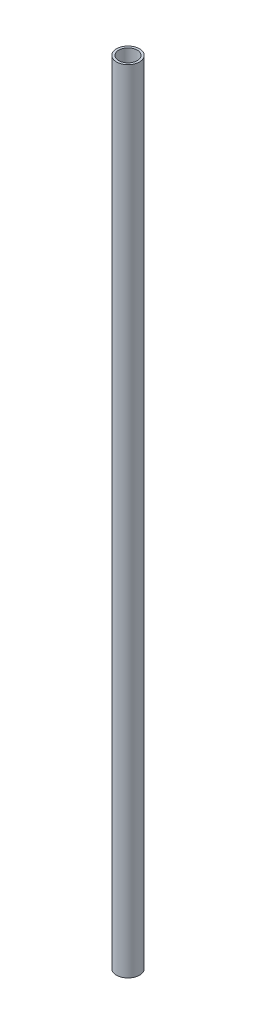
SolidWorks part; units mm, degrees
material "6061-T6 (SS)"
ref_plane "Front Plane" through (0, 0, 0) normal (0, 0, 1) x (1, 0, 0)
ref_plane "Top Plane" through (0, 0, 0) normal (0, 1, 0) x (1, 0, 0)
ref_plane "Right Plane" through (0, 0, 0) normal (1, 0, 0) x (0, 0, -1)
sketch "Sketch1" plane through (0, 0, 0) normal (0, 1, 0) x (1, 0, 0)
  circle A0 centre (0, 0) radius 6.35
  circle A1 centre (0, 0) radius 5.1054
  dimension "D1" = 12.7
  dimension "D2" = 10.2108
extrude "Boss-Extrude1" add sketch "Sketch1" along normal blind 438.15
ref_point "Point2"
